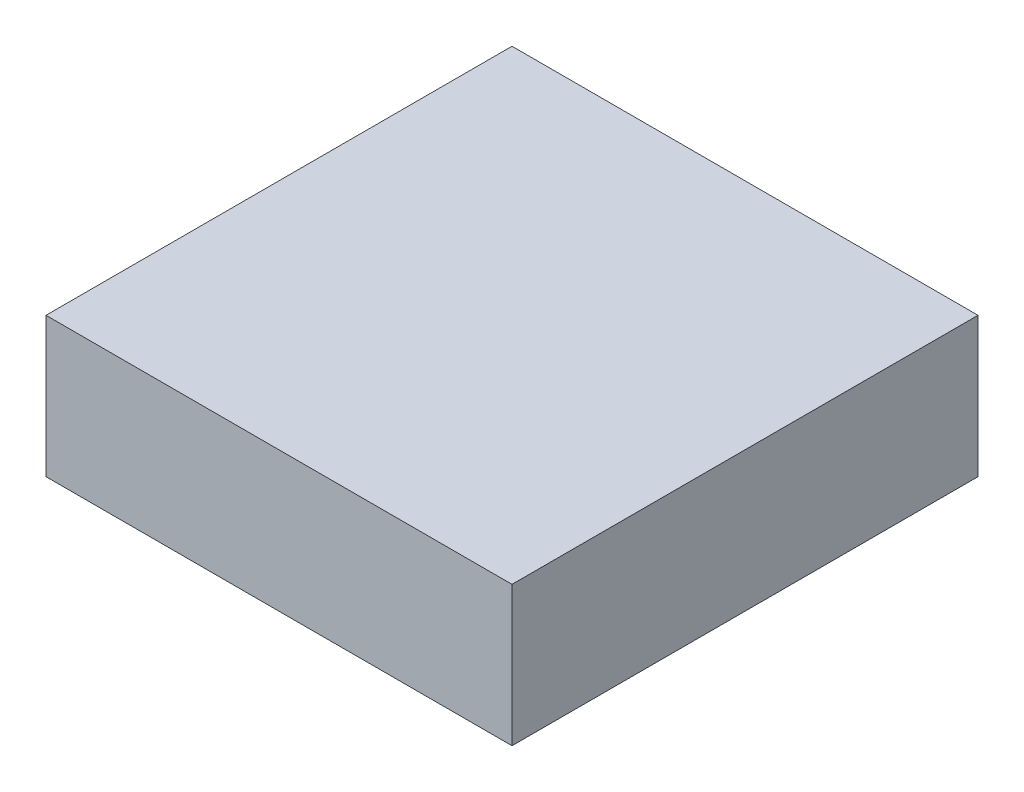
SolidWorks part; units mm, degrees
material "Rubber"
ref_plane "Front Plane" through (0, 0, 0) normal (0, 0, 1) x (1, 0, 0)
ref_plane "Top Plane" through (0, 0, 0) normal (0, 1, 0) x (1, 0, 0)
ref_plane "Right Plane" through (0, 0, 0) normal (1, 0, 0) x (0, 0, -1)
sketch "Sketch1" plane through (0, 0, 0) normal (0, 1, 0) x (1, 0, 0)
  line L1 (0, 0) -> (20, 0)
  line L2 (0, 0) -> (0, 20)
  line L3 (0, 20) -> (20, 20)
  line L4 (20, 0) -> (20, 20)
  dimension "D1" = 20
  dimension "D2" = 20
extrude "Boss-Extrude1" add sketch "Sketch1" along normal blind 6 contours L2 L1 L4 L3
